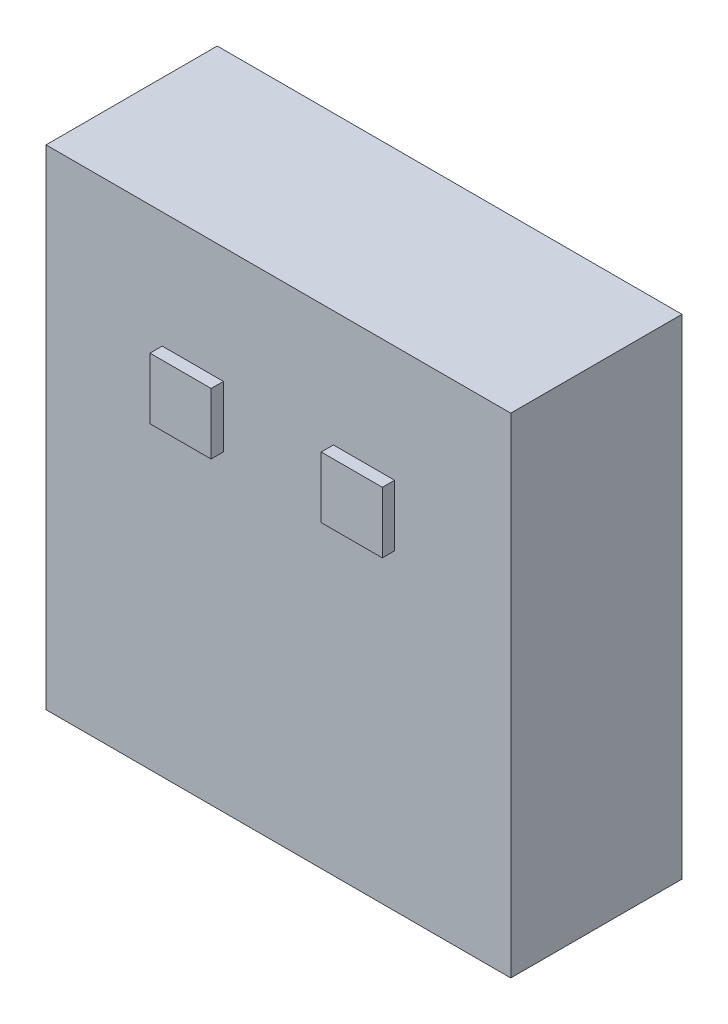
SolidWorks part; units mm, degrees
ref_plane "前视基准面" through (0, 0, 0) normal (0, 0, 1) x (1, 0, 0)
ref_plane "上视基准面" through (0, 0, 0) normal (0, 1, 0) x (1, 0, 0)
ref_plane "右视基准面" through (0, 0, 0) normal (1, 0, 0) x (0, 0, -1)
sketch "草图1" plane through (0, 0, 0) normal (0, 0, 1) x (1, 0, 0)
  line L1 (0, 0) -> (38, 0)
  line L2 (0, 0) -> (0, 40)
  line L3 (0, 40) -> (38, 40)
  line L4 (38, 0) -> (38, 40)
  dimension "D1" = 38
  dimension "D2" = 40
extrude "凸台-拉伸1" add sketch "草图1" along normal blind 14
sketch "草图2" plane through (0, 0, 14) normal (0, 0, 1) x (1, 0, 0)
  line L0 (38, 0) -> (38, 40) construction
  line L5 (23.5, 30.5) -> (28.5, 30.5)
  line L6 (23.5, 30.5) -> (23.5, 25.5)
  line L7 (23.5, 25.5) -> (28.5, 25.5)
  line L8 (28.5, 30.5) -> (28.5, 25.5)
  line L9 (38, 40) -> (0, 40) construction
  line L10 (19, 40) -> (19, 34.8962) construction
  line L11 (9.5, 30.5) -> (9.5, 25.5)
  line L12 (14.5, 25.5) -> (9.5, 25.5)
  line L13 (14.5, 30.5) -> (14.5, 25.5)
  line L14 (14.5, 30.5) -> (9.5, 30.5)
  point P8 (26, 30.5)
  point P11 (28.5, 28)
  dimension "D1" = 12
  dimension "D2" = 5
  dimension "D3" = 5
  dimension "D4" = 12
extrude "凸台-拉伸2" add sketch "草图2" along normal blind 1
